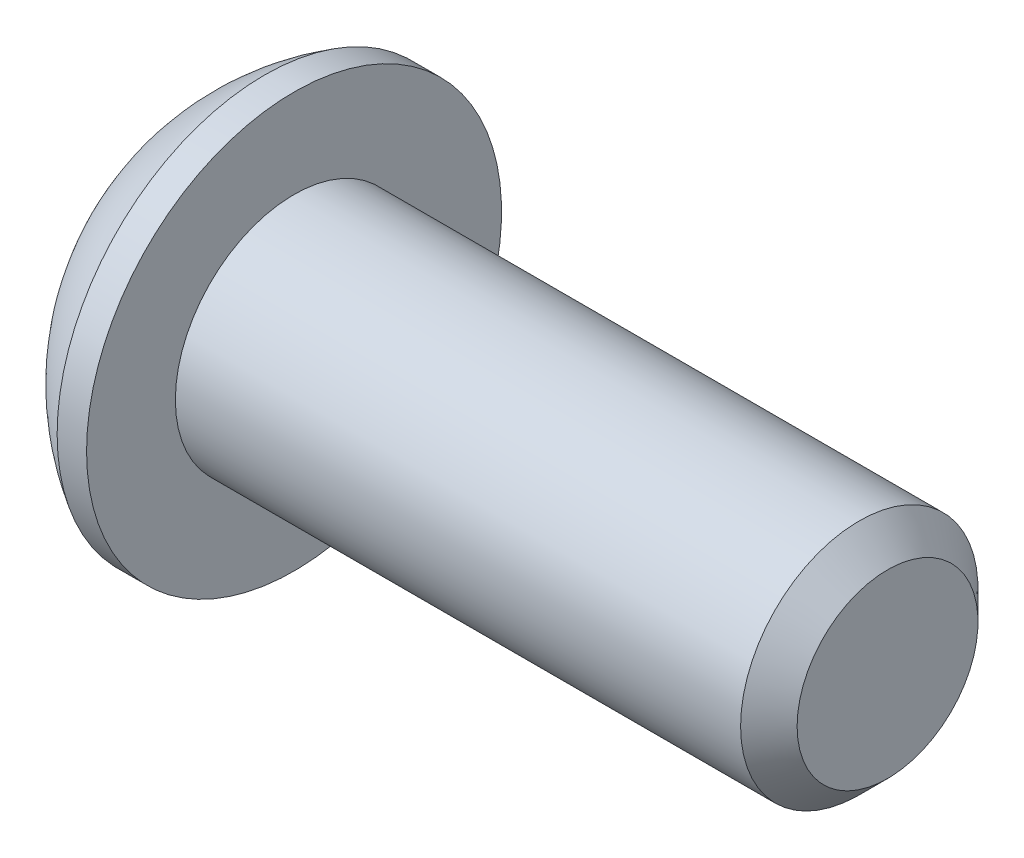
SolidWorks part; units mm, degrees
ref_plane "Plane1" through (0, 0, 0) normal (0, 0, 1) x (1, 0, 0)
ref_plane "Plane2" through (0, 0, 0) normal (0, 1, 0) x (1, 0, 0)
ref_plane "Plane3" through (0, 0, 0) normal (1, 0, 0) x (0, 0, -1)
sketch "BodySke" plane through (0, 0, 0) normal (0, 0, 1) x (1, 0, 0)
  line L0 (19.2278, 0) -> (19.2278, 2.4193)
  line L1 (18.4721, 3.175) -> (3.3528, 3.175)
  line L2 (3.3528, 3.175) -> (3.3528, 5.5499)
  line L3 (3.3528, 5.5499) -> (2.5654, 5.5499)
  line L4 (0, 0) -> (101.6, 0) construction
  line L5 (3.3528, -5.5499) -> (2.5654, -5.5499) construction
  line L6 (55.6768, -3.175) -> (3.3528, -3.175) construction
  line L7 (19.2278, 0) -> (0, 0)
  line L8 (0, 2.775) -> (0, -2.775) construction
  line L9 (0, 0) -> (0, 2.775)
  line L10 (19.2278, 2.4193) -> (18.4721, 3.175)
  line L11 (19.2278, -2.4193) -> (18.4721, -3.175) construction
  line L12 (4.6228, 9.525) -> (4.6228, -3.175) construction
  line L13 (3.3528, 9.525) -> (3.3528, -3.175) construction
  arc A1 (0, 2.775) -> (2.5654, 5.5499) centre (5.7851, 0) cw
  dimension "Diameter" = 6.35
  dimension "Length" = 15.875
  dimension "Head_dia" = 11.0998
  dimension "D1" = 5.5499
  dimension "Head_ht" = 3.3528
  dimension "Head_side_ht" = 0.7874
  dimension "Minor_dia" = 4.8387
  dimension "Body_ch_ang" = 45
  dimension "Advance" = 1.27
  dimension "Thread_nom" = 15.875
revolve "BaseBody" add sketch "BodySke" angle 360 about L4
cosmetic thread "ThreadCosmetic" [suppressed] parameters "Thread_length"=14.605, "Thread_minor"=4.8387
sketch "Sketch2" plane through (0, 0, 0) normal (0, 0, 1) x (1, 0, 0)
  line L0 (0, 1.9812) -> (2.2098, 1.9812)
  line L1 (2.2098, 1.9812) -> (3.3536, 0)
  line L3 (3.3536, 0) -> (0, 0)
  line L4 (0, 0) -> (0, 1.9812)
  line L5 (0, -1.9812) -> (2.2098, -1.9812) construction
  line L6 (0, 0) -> (47.625, 0) construction
  dimension "D2" = 60
  dimension "PreBroach_depth" = 2.2098
  dimension "PreBroach_dia" = 3.9624
revolve "PreBroach" cut sketch "Sketch2" angle 360 about L6
sketch "Sketch3" plane through (0, 0, 0) normal (1, 0, 0) x (0, 0, -1)
  line L0 (-1.9812, -1.1438) -> (-1.9812, 1.1438)
  line L1 (-1.9812, 1.1438) -> (0, 2.2877)
  line L2 (0, 2.2877) -> (1.9812, 1.1438)
  line L3 (1.9812, 1.1438) -> (1.9812, -1.1438)
  line L4 (1.9812, -1.1438) -> (0, -2.2877)
  line L5 (0, -2.2877) -> (-1.9812, -1.1438)
  dimension "Hex_size" = 3.9624
  dimension "D3" = 3.9624
  dimension "D1" = 1.9812
  dimension "D2" = 1.9812
extrude "Hex" cut sketch "Sketch3" along normal blind 2.2098
sketch "Sketch4" plane through (0, 9.525, 0) normal (1, 0, 0) x (0, 0, -1)
  line L0 (0, -9.525) -> (2.3876, -9.525)
  line L1 (0, -9.525) -> (6.1484, -5.9752) construction
  line L2 (0, -9.525) -> (1.1938, -7.4573)
  line L3 (1.9883, -8.949) -> (2.2704, -8.7861)
  line L4 (1.493, -8.0911) -> (1.7751, -7.9282)
  arc A0 (1.9883, -8.949) -> (1.493, -8.0911) centre (0, -9.525) ccw
  arc A1 (2.3876, -9.525) -> (2.2704, -8.7861) centre (0, -9.525) ccw
  arc A2 (1.1938, -7.4573) -> (1.7751, -7.9282) centre (0, -9.525) cw
  dimension "Spline_n_dim" = 4.1402
  dimension "Spline_m_dim" = 4.7752
  dimension "D1" = 30
  dimension "D2" = 60
  dimension "Spline_p_dim" = 0.9906
  dimension "D3" = 0.4953
extrude "Spline" [suppressed] cut sketch "Sketch4" along normal blind 2.2098
pattern_circular "CirPattern1" [suppressed] count 6 every 60 about axis through (0, 0, 0) along (1, 0, 0)
sketch "ThdSchSke" plane through (0, 0, 0) normal (0, 0, 1) x (1, 0, 0)
  line L0 (4.6228, -2.4193) -> (4.0937, -3.175)
  line L1 (4.6228, -2.4193) -> (5.1519, -3.175)
  line L2 (5.1519, -3.175) -> (5.1519, -3.9688)
  line L3 (-3.175, 0) -> (5.1513, 0) construction
  line L5 (5.1519, -3.9688) -> (4.0937, -3.9688)
  line L6 (4.0937, -3.9688) -> (4.0937, -3.175)
  dimension "Diameter" = 6.35
  dimension "Thread_minor" = 4.8387
  dimension "SideAngle" = 55
  dimension "VeeAngle" = 70
  dimension "Overcut" = 7.9375
  dimension "Start" = 4.6228
revolve "ThreadSchematic" [suppressed] cut sketch "ThdSchSke" angle 360 about L3
pattern_linear "ThdSchPat" [suppressed]
equation "\"D1@BodySke\" = \"Head_dia@BodySke\" * .5"
equation "\"Thread_minor@ThreadCosmetic\" = \"Minor_dia@BodySke\""
equation "\"D1@Sketch3\" = \"Hex_size@Sketch3\" / 2"
equation "\"D2@Sketch3\" = \"D1@Sketch3\""
equation "\"D3@Sketch3\" = \"Hex_size@Sketch3\""
equation "\"D3@Sketch4\" = \"Spline_p_dim@Sketch4\" / 2"
equation "\"D1@Sketch4\" = \"D2@Sketch4\" / 2"
equation "\"Thread_length@ThreadCosmetic\" = ((sgn( (\"Length@BodySke\" - \"Advance@BodySke\" ) - \"Thread_nom@BodySke\" )-1)*( (\"Length@BodySke\" - \"Advance@BodySke\" ) - \"Thread_nom@BodySke\" ))/-2+ \"Thread_nom@BodySke\""
equation "\"Thread_minor@ThdSchSke\" = \"Minor_dia@BodySke\""
equation "\"Diameter@ThdSchSke\" = \"Diameter@BodySke\""
equation "\"Overcut@ThdSchSke\" = \"Diameter@BodySke\" * 1.25"
equation "\"Start@ThdSchSke\" = \"Head_ht@BodySke\" + \"Length@BodySke\" - \"Thread_length@ThreadCosmetic\"  '---Non-countersunk---"
equation "\"Num_threads@ThdSchPat\" = int( \"Thread_length@ThreadCosmetic\" / \"Advance@BodySke\" + 0.999 )  + 1"
equation "\"Advance@ThdSchPat\" = \"Thread_length@ThreadCosmetic\" /  (\"Num_threads@ThdSchPat\" - 1) 'relax it"
equation "\"Num_threads@ThdSchPat\" = \"Num_threads@ThdSchPat\" - sgn( \"Num_threads@ThdSchPat\" - 1) '---chamfered tips only---"
